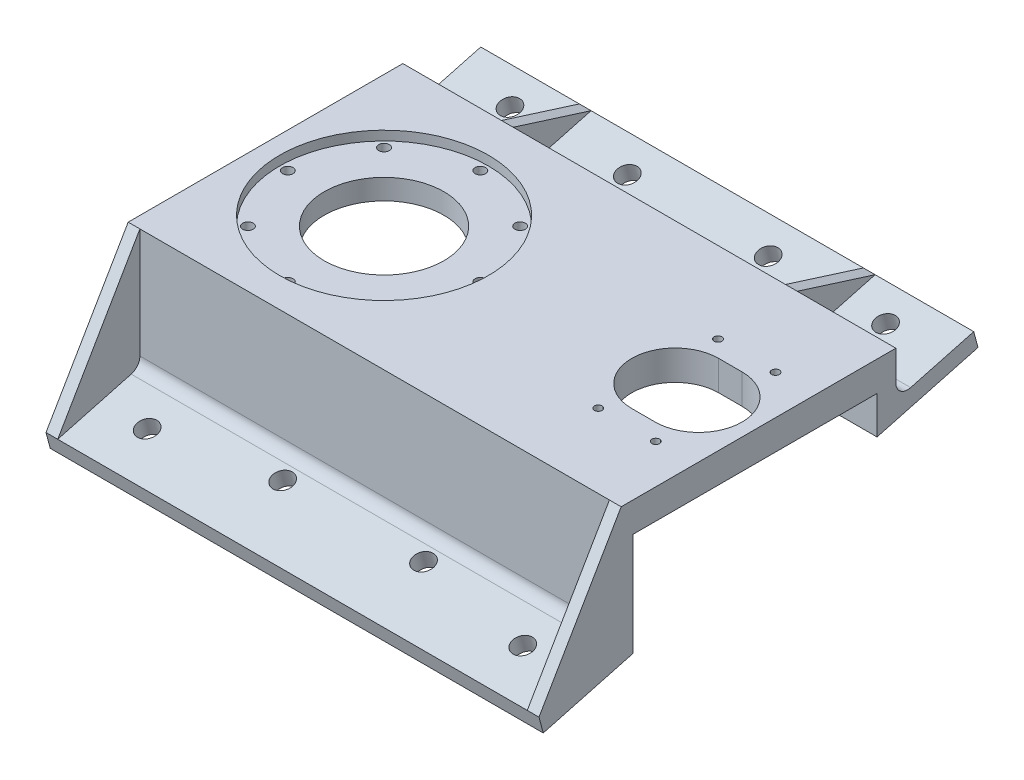
SolidWorks part; units mm, degrees
other "标注1"
sketch "草图25" plane through (-52, 30, -95) normal (-0.4172, 0.7166, -0.559) x (-0.8994, -0.2372, 0.3671)
other "标注2"
sketch "草图26" plane through (-52, 30, -95) normal (-0.4172, 0.7166, -0.559) x (-0.8994, -0.2372, 0.3671)
material "1060 合金"
ref_plane "前视基准面" through (0, 0, 0) normal (0, 0, 1) x (1, 0, 0)
ref_plane "上视基准面" through (0, 0, 0) normal (0, 1, 0) x (1, 0, 0)
ref_plane "右视基准面" through (0, 0, 0) normal (1, 0, 0) x (0, 0, -1)
sketch "草图1" plane through (0, 0, 0) normal (0, 1, 0) x (1, 0, 0)
  line L0 (0, 0) -> (170, 0) construction
  line L1 (170, 31.93) -> (170, -31.93)
  line L2 (15.8391, 73.3084) -> (162.1119, 41.7045)
  line L3 (15.8391, -73.3084) -> (162.1119, -41.7045)
  arc A0 (15.8391, 73.3084) -> (15.8391, -73.3084) centre (0, 0) ccw
  arc A1 (162.1119, -41.7045) -> (170, -31.93) centre (160, -31.93) ccw
  arc A2 (170, 31.93) -> (162.1119, 41.7045) centre (160, 31.93) ccw
  point P6 (170, 0)
  dimension "D1" = 150
  dimension "D4" = 20
  dimension "D5" = 20
  dimension "D2" = 170
  dimension "D3" = 63.86
extrude "凸台-拉伸1" add sketch "草图1" along normal blind 30
sketch "草图2" plane through (0, 30, 0) normal (0, 1, 0) x (1, 0, 0)
  circle A0 centre (0, 0) radius 44.45
  dimension "D1" = 88.9
extrude "切除-拉伸1" cut sketch "草图2" against normal blind 4
sketch "草图3" plane through (0, 26, 0) normal (0, 1, 0) x (1, 0, 0)
  line L0 (0, 0) -> (0, 90.3276) construction
  circle A0 centre (0, 0) radius 25.5
  circle A1 centre (0, 41) radius 2.25
  circle A2 centre (28.9914, 28.9914) radius 2.25
  circle A3 centre (41, 0) radius 2.25
  circle A4 centre (28.9914, -28.9914) radius 2.25
  circle A5 centre (0, -41) radius 2.25
  circle A6 centre (-28.9914, -28.9914) radius 2.25
  circle A7 centre (-41, 0) radius 2.25
  circle A8 centre (-28.9914, 28.9914) radius 2.25
  dimension "D1" = 51
  dimension "D3" = 4.5
  dimension "D2" = 41
  dimension "D4" = 8
extrude "切除-拉伸2" cut sketch "草图3" against normal through all contours A2 | A3 | A4 | A5 | A6 | A7 | A8 | A1 | A0
sketch "草图4" plane through (0, 30, 0) normal (0, 1, 0) x (1, 0, 0)
  line L0 (0, 0) -> (134, 0) construction
  line L1 (124, 18.5) -> (134, 18.5)
  line L2 (124, -18.5) -> (134, -18.5)
  arc A0 (134, -18.5) -> (134, 18.5) centre (134, 0) ccw
  arc A1 (124, 18.5) -> (124, -18.5) centre (124, 0) ccw
  dimension "D2" = 37
  dimension "D3" = 37
  dimension "D1" = 134
  dimension "D4" = 10
extrude "切除-拉伸3" cut sketch "草图4" against normal through all
sketch "草图5" plane through (0, 30, 0) normal (0, 1, 0) x (1, 0, 0)
  arc A0 (134, -18.5) -> (134, 18.5) centre (134, 0) ccw construction
  arc A1 (124, 18.5) -> (124, -18.5) centre (124, 0) ccw construction
  arc A2 (134, -18.5) -> (134, 18.5) centre (134, 0) ccw construction
  arc A3 (124, 18.5) -> (124, -18.5) centre (124, 0) ccw construction
  circle A4 centre (116.75, 25.5) radius 1.65
  circle A5 centre (141.25, 25.5) radius 1.65
  circle A6 centre (141.25, -25.5) radius 1.65
  circle A7 centre (116.75, -25.5) radius 1.65
  dimension "D1" = 3.3
  dimension "D2" = 3.3
  dimension "D3" = 3.3
  dimension "D4" = 3.3
  dimension "D7" = 25.5
  dimension "D5" = 7.25
  dimension "D6" = 25.5
  dimension "D8" = 7.25
  dimension "D9" = 7.25
extrude "切除-拉伸4" cut sketch "草图5" against normal through all
sketch "草图6" plane through (0, 30, 0) normal (0, 1, 0) x (1, 0, 0)
  line L0 (158, 42.5929) -> (158, -42.5929) construction
  line L2 (-52, 54.0463) -> (-52, -54.0463) construction
  line L6 (162.1119, 41.7045) -> (15.8391, 73.3084) construction
  line L7 (15.8391, -73.3084) -> (162.1119, -41.7045) construction
  line L8 (-52, 95) -> (-52, -95)
  line L9 (158, 95) -> (158, -95)
  line L10 (-52, 95) -> (158, 95)
  line L11 (-52, -95) -> (158, -95)
  line L15 (162.1119, 41.7045) -> (15.8391, 73.3084)
  line L16 (15.8391, -73.3084) -> (162.1119, -41.7045)
  line L17 (170, -31.93) -> (170, 31.93)
  line L18 (162.1119, 41.7045) -> (15.8391, 73.3084)
  line L19 (15.8391, -73.3084) -> (162.1119, -41.7045)
  line L20 (170, -31.93) -> (170, 31.93)
  arc A0 (15.8391, 73.3084) -> (15.8391, -73.3084) centre (0, 0) ccw construction
  arc A6 (170, 31.93) -> (162.1119, 41.7045) centre (160, 31.93) ccw
  arc A7 (15.8391, 73.3084) -> (15.8391, -73.3084) centre (0, 0) ccw
  arc A8 (162.1119, -41.7045) -> (170, -31.93) centre (160, -31.93) ccw
  arc A9 (170, 31.93) -> (162.1119, 41.7045) centre (160, 31.93) ccw
  arc A10 (15.8391, 73.3084) -> (15.8391, -73.3084) centre (0, 0) ccw
  arc A11 (162.1119, -41.7045) -> (170, -31.93) centre (160, -31.93) ccw
  point P8 (-52, 0)
  point P13 (158, 0)
  line M26 (162.1119, 41.7045) -> (15.8391, 73.3084)
  arc M27 (15.8391, 73.3084) -> (15.8391, -73.3084) centre (0, 0) ccw
  line M28 (15.8391, -73.3084) -> (162.1119, -41.7045)
  dimension "D3" = 190
  dimension "D1" = 210
  dimension "D2" = 52
  dimension "D4" = 190
  dimension "D5" = 0
extrude "凸台-拉伸2" add sketch "草图6" against normal blind 30 contours L10 L8 L9 M27 M26 | L8 L11 L9 M28 M27
sketch "草图7" plane through (0, 30, 0) normal (0, 1, 0) x (1, 0, 0)
  line L0 (-52, 54.0463) -> (-52, -54.0463)
  line L1 (158, 42.5929) -> (158, -42.5929)
  line L9 (162.1119, 41.7045) -> (158, 42.5929)
  line L10 (158, 42.5929) -> (158, 95)
  line L11 (158, 95) -> (-52, 95)
  line L12 (-52, 95) -> (-52, 54.0463)
  line L13 (-52, -54.0463) -> (-52, -95)
  line L14 (-52, -95) -> (158, -95)
  line L15 (158, -95) -> (158, -42.5929)
  line L16 (158, -42.5929) -> (162.1119, -41.7045)
  line L17 (170, -31.93) -> (170, 31.93)
  line L18 (162.1119, 41.7045) -> (158, 42.5929)
  line L21 (-52, 95) -> (-52, 54.0463)
  line L25 (158, -42.5929) -> (162.1119, -41.7045)
  line L26 (170, -31.93) -> (170, 31.93)
  arc A3 (170, 31.93) -> (162.1119, 41.7045) centre (160, 31.93) ccw
  arc A4 (-52, 54.0463) -> (-52, -54.0463) centre (0, 0) ccw
  arc A5 (162.1119, -41.7045) -> (170, -31.93) centre (160, -31.93) ccw
  arc A6 (170, 31.93) -> (162.1119, 41.7045) centre (160, 31.93) ccw
  arc A7 (-52, 54.0463) -> (-52, -54.0463) centre (0, 0) ccw
  arc A8 (162.1119, -41.7045) -> (170, -31.93) centre (160, -31.93) ccw
  arc M22 (170, 31.93) -> (162.1119, 41.7045) centre (160, 31.93) ccw
  line M23 (162.1119, 41.7045) -> (158, 42.5929)
  arc M27 (-52, 54.0463) -> (-52, -54.0463) centre (0, 0) ccw
  line M31 (158, -42.5929) -> (162.1119, -41.7045)
  arc M32 (162.1119, -41.7045) -> (170, -31.93) centre (160, -31.93) ccw
  line M33 (170, -31.93) -> (170, 31.93)
  dimension "D1" = 0
extrude "切除-拉伸5" cut sketch "草图7" against normal through all contours L0 M27 | L1 M23 M31 M32 M33 M22
sketch "草图9" plane through (-52, 0, 0) normal (-1, 0, 0) x (0, 0, 1)
  line L0 (-95, 20) -> (-60, 10.6218)
  line L1 (-95, 30) -> (95, 30) construction
  line L3 (-60, 10.6218) -> (-60, 30)
  line L5 (-95, 0) -> (-95, 30) construction
  line L7 (-95, 20) -> (-95, 30)
  line L8 (-95, 30) -> (-60, 30)
  dimension "D1" = 15
  dimension "D3" = 19.3782
  dimension "D4" = 35
  dimension "D5" = 10
extrude "切除-拉伸7" cut sketch "草图9" against normal through all contours L8 L3 L0 L7
sketch "草图8" plane through (-52, 0, 0) normal (-1, 0, 0) x (0, 0, 1)
  line L0 (0, 0) -> (52, 0)
  line L1 (-95, 0) -> (95, 0) construction
  line L2 (52, 0) -> (52, 17.3)
  line L3 (52, 17.3) -> (-52, 17.3)
  line L4 (-52, 17.3) -> (-52, 0)
  line L5 (-52, 0) -> (0, 0)
  line L6 (-60, 30) -> (95, 30) construction
  dimension "D1" = 52
  dimension "D2" = 52
  dimension "D3" = 12.7
sketch "草图10" plane through (-52, 0, 0) normal (-1, 0, 0) x (0, 0, 1)
  line L0 (-95, 12.7531) -> (-47.4049, 0) construction
  line L1 (-95, 0) -> (-95, 20) construction
  line L2 (-95, 0) -> (95, 0) construction
  line L3 (-95, 20) -> (-60, 10.6218) construction
  line L6 (-95, 12.7531) -> (-52, 1.2313)
  line L7 (-52, 1.2313) -> (-52, 0)
  line L8 (-95, 12.7531) -> (-95, 0)
  line L9 (-95, 0) -> (-52, 0)
  line L10 (-52, 17.3) -> (-52, 0) construction
  dimension "D1" = 7
extrude "切除-拉伸8" cut sketch "草图10" against normal through all
extrude "切除-拉伸9" cut sketch "草图8" against normal through all
fillet "圆角1" radius 5 1 edges at (53, 10.6218, -60)
sketch "草图11" plane through (-52, 0, 0) normal (-1, 0, 0) x (0, 0, 1)
  line L0 (-95, 12.7531) -> (-93.1883, 19.5145)
  line L1 (-95, 20) -> (-66.2941, 12.3083) construction
  line L2 (-93.1883, 19.5145) -> (-95, 20)
  line L3 (-95, 20) -> (-95, 12.7531)
extrude "切除-拉伸10" cut sketch "草图11" against normal through all
sketch "草图12" plane through (-52, 0, 0) normal (-1, 0, 0) x (0, 0, 1)
  line L0 (-93.1883, 19.5145) -> (-60, 30)
  line L10 (-93.1883, 19.5145) -> (-95, 12.7531)
  line L11 (-95, 12.7531) -> (-52, 1.2313)
  line L12 (-52, 1.2313) -> (-52, 17.3)
  line L13 (-52, 17.3) -> (52, 17.3)
  line L14 (52, 17.3) -> (52, 0)
  line L15 (52, 0) -> (95, 0)
  line L16 (95, 0) -> (95, 30)
  line L17 (95, 30) -> (-60, 30)
  line L18 (-60, 30) -> (-60, 17.1379)
  line L19 (-66.2941, 12.3083) -> (-93.1883, 19.5145)
  line L28 (-60, 30) -> (-60, 17.1379)
  line L29 (-66.2941, 12.3083) -> (-93.1883, 19.5145)
  arc A1 (-66.2941, 12.3083) -> (-60, 17.1379) centre (-65, 17.1379) ccw
  arc A2 (-66.2941, 12.3083) -> (-60, 17.1379) centre (-65, 17.1379) ccw
  dimension "D1" = 0
extrude "凸台-拉伸3" add sketch "草图12" against normal blind 5
sketch "草图13" plane through (158, 0, 0) normal (1, 0, 0) x (0, 0, -1)
  line L3 (66.2941, 12.3083) -> (93.1883, 19.5145)
  line L4 (93.1883, 19.5145) -> (60, 30)
  line L5 (60, 30) -> (60, 17.1379)
  line L6 (66.2941, 12.3083) -> (93.1883, 19.5145)
  line L7 (93.1883, 19.5145) -> (60, 30)
  line L8 (60, 30) -> (60, 17.1379)
  arc A1 (60, 17.1379) -> (66.2941, 12.3083) centre (65, 17.1379) ccw
  arc A2 (60, 17.1379) -> (66.2941, 12.3083) centre (65, 17.1379) ccw
  dimension "D1" = 0
extrude "凸台-拉伸4" add sketch "草图13" against normal blind 5
sketch "草图14" plane through (0, -5.0897, -1.3638) normal (0, 0.9659, 0.2588) x (1, 0, 0)
  line L0 (153, 67.2208) -> (153, 95.0637) construction
  line L3 (153, 95.0637) -> (-47, 95.0637) construction
  circle A0 centre (-27, 82.0637) radius 4.25
  circle A1 centre (23, 82.0637) radius 4.25
  circle A2 centre (83, 82.0637) radius 4.25
  circle A3 centre (133, 82.0637) radius 4.25
  dimension "D1" = 8.5
  dimension "D2" = 160
  dimension "D3" = 20
  dimension "D4" = 50
  dimension "D5" = 50
  dimension "D6" = 13
extrude "切除-拉伸11" cut sketch "草图14" against normal through all
sketch "草图16" plane through (-52, 0, 0) normal (-1, 0, 0) x (0, 0, 1)
  line L0 (-60, 30) -> (95, 30) construction
  line L1 (95, 0) -> (52, 0)
  line L2 (95, 0) -> (95, 30)
  line L3 (95, 30) -> (52, 30)
  line L4 (52, 0) -> (52, 30)
extrude "切除-拉伸12" cut sketch "草图16" against normal through all
ref_plane "基准面1" through (0, -11.8512, -3.1755) normal (0, -0.9659, -0.2588) x (-1, 0, 0)
sketch "草图18" plane through (0, 30, 0) normal (0, 1, 0) x (1, 0, 0)
  line L1 (-52, -52) -> (158, -52)
  line L2 (-52, -52) -> (-52, -57)
  line L3 (-52, -57) -> (158, -57)
  line L4 (158, -52) -> (158, -57)
  dimension "D1" = 5
extrude "凸台-拉伸7" add sketch "草图18" against normal up to surface (56.6355 mm away) up to plane "基准面1"
sketch "草图19" plane through (-52, 0, 0) normal (-1, 0, 0) x (0, 0, 1)
  line L0 (57, -27.9752) -> (90.1883, -36.868)
  line L1 (90.1883, -36.868) -> (92, -30.1065)
  line L2 (92, -30.1065) -> (57, -20.7283)
  line L3 (57, -27.9752) -> (57, 30) construction
  line L4 (57, -20.7283) -> (57, -27.9752)
  line L5 (52, -26.6355) -> (57, -27.9752) construction
  dimension "D1" = 7
  dimension "D2" = 40
extrude "凸台-拉伸8" add sketch "草图19" against normal up to surface (210 mm away) up to face at (158, 8.1654, -14.9098)
sketch "草图20" plane through (-52, 0, 0) normal (-1, 0, 0) x (0, 0, 1)
  line L0 (92, -30.1065) -> (57, -20.7283) construction
  line L1 (57, -20.7283) -> (57, 30) construction
  line L2 (92, -30.1065) -> (57, -20.7283)
  line L3 (57, -20.7283) -> (57, 30)
  line L4 (57, 30) -> (92, -30.1065)
extrude "凸台-拉伸9" add sketch "草图20" against normal blind 5
sketch "草图21" plane through (158, 0, 0) normal (1, 0, 0) x (0, 0, -1)
  line L3 (-57, 30) -> (-92, -30.1065)
  line L4 (-92, -30.1065) -> (-57, -20.7283)
  line L5 (-57, -20.7283) -> (-57, 30)
  line L6 (-57, 30) -> (-92, -30.1065)
  line L7 (-92, -30.1065) -> (-57, -20.7283)
  line L8 (-57, -20.7283) -> (-57, 30)
  dimension "D1" = 0
extrude "凸台-拉伸10" add sketch "草图21" against normal blind 5
sketch "草图22" plane through (0, -5.0897, -1.3638) normal (0, 0.9659, 0.2588) x (1, 0, 0)
  line L0 (-47, -96.6573) -> (-47, -47.2932) construction
  line L2 (153, -96.6573) -> (153, -60.4226) construction
  circle A0 centre (-27, -77.9363) radius 4.25
  circle A1 centre (23, -69.9363) radius 4.25
  circle A2 centre (83, -69.9363) radius 4.25
  circle A3 centre (133, -77.9363) radius 4.25
  circle A4 centre (133, 82.0637) radius 4.25 construction
  circle A5 centre (-27, 82.0637) radius 4.25 construction
  circle A6 centre (23, 82.0637) radius 4.25 construction
  circle A7 centre (83, 82.0637) radius 4.25 construction
  dimension "D1" = 8.5
  dimension "D7" = 152
  dimension "D6" = 152
  dimension "D8" = 50
  dimension "D4" = 160
  dimension "D5" = 160
  dimension "D2" = 20
  dimension "D3" = 20
  dimension "D9" = 50
extrude "切除-拉伸13" cut sketch "草图22" against normal through all
fillet "圆角2" radius 5 1 edges at (53, -20.7283, 57)
ref_plane "基准面2" through (113.5, 0, 0) normal (1, 0, 0) x (0, 0, -1)
sketch "草图27" plane through (113.5, 0, 0) normal (1, 0, 0) x (0, 0, -1)
  line L3 (60, 30) -> (60, 17.1379)
  line L4 (93.1883, 19.5145) -> (60, 30)
  line L5 (66.2941, 12.3083) -> (93.1883, 19.5145)
  line L6 (60, 30) -> (60, 17.1379)
  line L7 (93.1883, 19.5145) -> (60, 30)
  line L8 (66.2941, 12.3083) -> (93.1883, 19.5145)
  arc A1 (60, 17.1379) -> (66.2941, 12.3083) centre (65, 17.1379) ccw
  arc A2 (60, 17.1379) -> (66.2941, 12.3083) centre (65, 17.1379) ccw
  dimension "D1" = 0
extrude "凸台-拉伸11" add sketch "草图27" along normal mid plane 5
sketch "草图29" plane through (153, 0, 0) normal (-1, 0, 0) x (0, 0, 1)
  line L3 (-60, 17.1379) -> (-60, 30)
  line L4 (-60, 30) -> (-93.1883, 19.5145)
  line L5 (-93.1883, 19.5145) -> (-66.2941, 12.3083)
  line L6 (-60, 17.1379) -> (-60, 30)
  line L7 (-60, 30) -> (-93.1883, 19.5145)
  line L8 (-93.1883, 19.5145) -> (-66.2941, 12.3083)
  arc A1 (-66.2941, 12.3083) -> (-60, 17.1379) centre (-65, 17.1379) ccw
  arc A2 (-66.2941, 12.3083) -> (-60, 17.1379) centre (-65, 17.1379) ccw
  dimension "D1" = 0
extrude "切除-拉伸16" cut sketch "草图29" against normal blind 5
ref_plane "基准面3" through (-7.5, 0, 0) normal (-1, 0, 0) x (0, 0, 1)
sketch "草图30" plane through (-7.5, 0, 0) normal (-1, 0, 0) x (0, 0, 1)
  line L5 (-93.1883, 19.5145) -> (-66.2941, 12.3083)
  line L6 (-60, 30) -> (-93.1883, 19.5145)
  line L7 (-60, 17.1379) -> (-60, 30)
  line L10 (-93.1883, 19.5145) -> (-66.2941, 12.3083)
  line L11 (-60, 30) -> (-93.1883, 19.5145)
  line L12 (-60, 17.1379) -> (-60, 30)
  arc A1 (-66.2941, 12.3083) -> (-60, 17.1379) centre (-65, 17.1379) ccw
  arc A2 (-66.2941, 12.3083) -> (-60, 17.1379) centre (-65, 17.1379) ccw
  dimension "D1" = 0
extrude "凸台-拉伸12" add sketch "草图30" along normal mid plane 5
sketch "草图31" plane through (-47, 0, 0) normal (1, 0, 0) x (0, 0, -1)
  line L5 (66.2941, 12.3083) -> (93.1883, 19.5145)
  line L6 (93.1883, 19.5145) -> (60, 30)
  line L7 (60, 30) -> (60, 17.1379)
  line L10 (66.2941, 12.3083) -> (93.1883, 19.5145)
  line L11 (93.1883, 19.5145) -> (60, 30)
  line L12 (60, 30) -> (60, 17.1379)
  arc A1 (60, 17.1379) -> (66.2941, 12.3083) centre (65, 17.1379) ccw
  arc A2 (60, 17.1379) -> (66.2941, 12.3083) centre (65, 17.1379) ccw
  dimension "D1" = 0
extrude "切除-拉伸18" cut sketch "草图31" against normal blind 5
